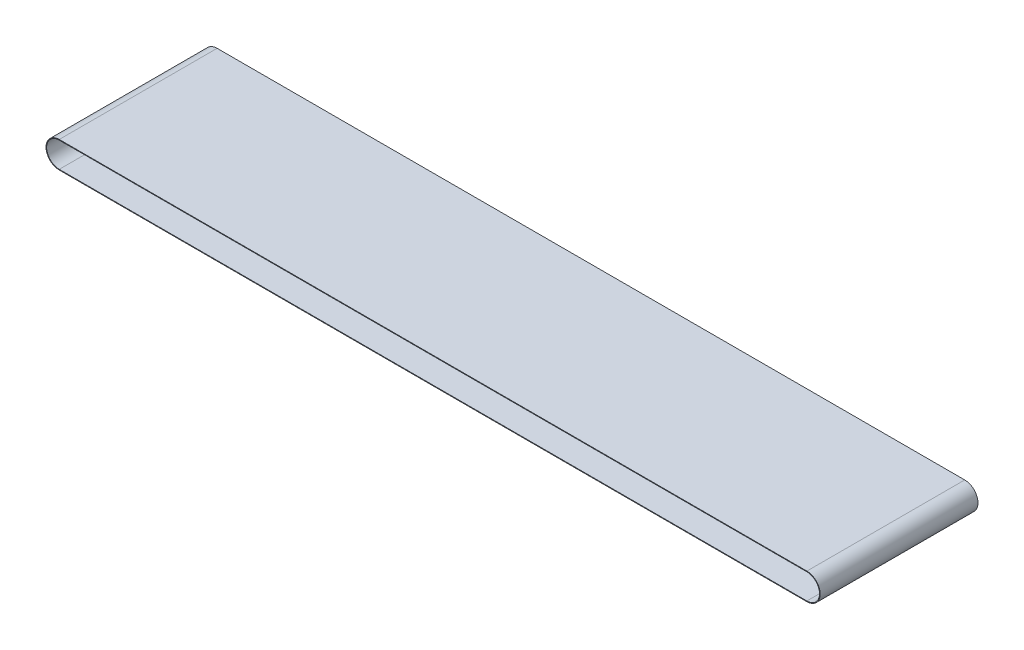
SolidWorks part; units mm, degrees
material "PVC rigido"
ref_plane "Piano frontale" through (0, 0, 0) normal (0, 0, 1) x (1, 0, 0)
ref_plane "Piano superiore" through (0, 0, 0) normal (0, 1, 0) x (1, 0, 0)
ref_plane "Piano destro" through (0, 0, 0) normal (1, 0, 0) x (0, 0, -1)
sketch "Schizzo1" plane through (0, 0, 0) normal (0, 0, 1) x (1, 0, 0)
  line L0 (-1184.025, 0) -> (1184.025, 0) construction
  line L1 (-1184.025, 40) -> (1184.025, 40)
  line L2 (0, 40) -> (0, -40) construction
  line L3 (-1184.025, -40) -> (1184.025, -40)
  line L4 (-1184.025, 42) -> (1184.025, 42)
  line L5 (-1184.025, -42) -> (1184.025, -42)
  arc A0 (-1184.025, 40) -> (-1184.025, -40) centre (-1184.025, 0) ccw
  arc A1 (1184.025, 40) -> (1184.025, -40) centre (1184.025, 0) cw
  arc A2 (1184.025, 42) -> (1184.025, -42) centre (1184.025, 0) cw
  arc A3 (-1184.025, 42) -> (-1184.025, -42) centre (-1184.025, 0) ccw
  dimension "D1" = 80
  dimension "D2" = 2368.05
  dimension "D3" = 2
extrude "Estrusione1" add sketch "Schizzo1" along normal mid plane 500
